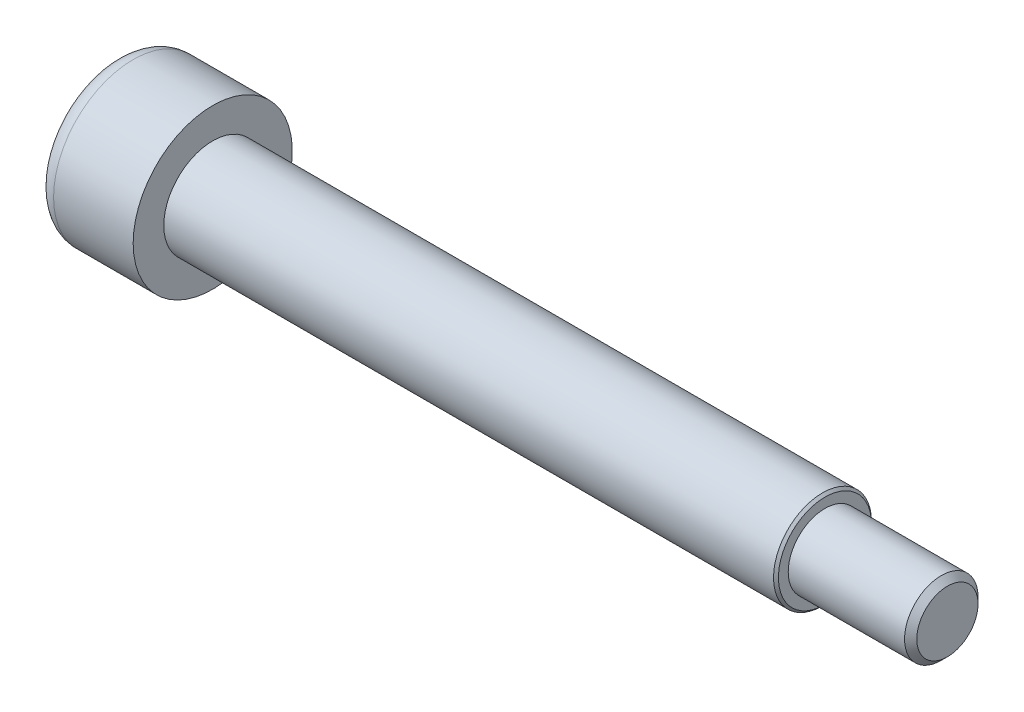
SolidWorks part; units mm, degrees
ref_plane "Face" through (0, 0, 0) normal (0, 0, 1) x (1, 0, 0)
ref_plane "Dessus" through (0, 0, 0) normal (0, 1, 0) x (1, 0, 0)
ref_plane "Droite" through (0, 0, 0) normal (1, 0, 0) x (0, 0, -1)
sketch "Esquisse1" plane through (0, 0, 0) normal (0, 0, 1) x (1, 0, 0)
  line L0 (0, 0) -> (66.365, 0) construction
  line L1 (60, 0) -> (60, -3)
  line L2 (60, -3) -> (50, -3)
  line L3 (0, -4) -> (0, -6.5)
  line L4 (0, -6.5) -> (-8, -6.5)
  line L5 (-8, -6.5) -> (-8, 0)
  line L6 (-8, 0) -> (60, 0)
  line L7 (50, -3) -> (50, -4)
  line L8 (50, -4) -> (0, -4)
  dimension "D1" = 8
  dimension "D2" = 6.5
  dimension "D3" = 50
  dimension "D4" = 3
  dimension "D5" = 10
  dimension "D6" = 4
revolve "Base-Révolution" add sketch "Esquisse1" angle 360 about L0
chamfer "Chanfrein1" distance 0.5 angle 45
fillet "Congé1" radius 1.5
chamfer "Chanfrein2" distance 0.2 angle 45
